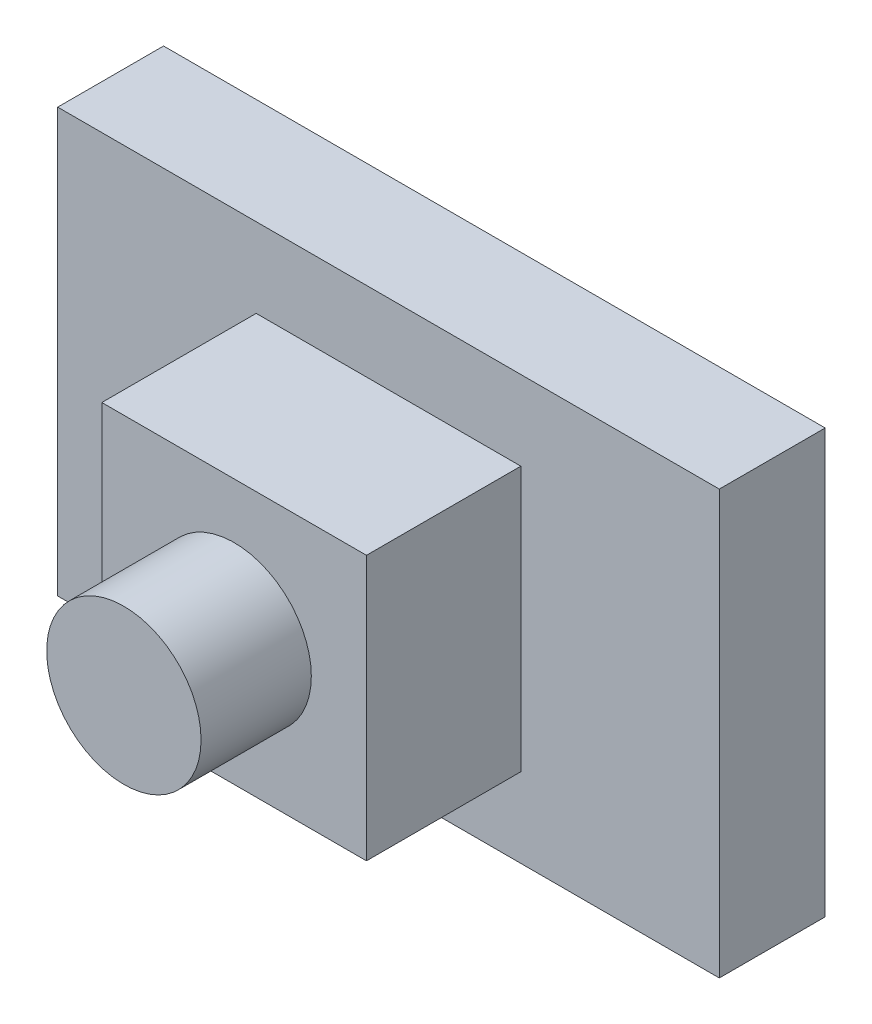
SolidWorks part; units mm, degrees
ref_plane "Ön Düzlem" through (0, 0, 0) normal (0, 0, 1) x (1, 0, 0)
ref_plane "Üst Düzlem" through (0, 0, 0) normal (0, 1, 0) x (1, 0, 0)
ref_plane "Sağ Düzlem" through (0, 0, 0) normal (1, 0, 0) x (0, 0, -1)
sketch "Çizim2" plane through (0, 0, 0) normal (0, 0, 1) x (1, 0, 0)
  line L1 (-7.5, -4.8) -> (7.5, -4.8)
  line L2 (-7.5, -4.8) -> (-7.5, 4.8)
  line L3 (-7.5, 4.8) -> (7.5, 4.8)
  line L4 (7.5, -4.8) -> (7.5, 4.8)
  line L5 (-7.5, -4.8) -> (7.5, 4.8) construction
  line L6 (-7.5, 4.8) -> (7.5, -4.8) construction
  point P0 (0, 0)
  dimension "D1" = 15
  dimension "D2" = 9.6
extrude "Yükseklik-Ekstrüzyon1" add sketch "Çizim2" along normal blind 2.4
sketch "Çizim3" plane through (0, 0, 2.4) normal (0, 0, 1) x (1, 0, 0)
  line L1 (-3, -3) -> (3, -3)
  line L2 (-3, -3) -> (-3, 3)
  line L3 (-3, 3) -> (3, 3)
  line L4 (3, -3) -> (3, 3)
  line L5 (-3, -3) -> (3, 3) construction
  line L6 (-3, 3) -> (3, -3) construction
  point P0 (0, 0)
  dimension "D1" = 6
  dimension "D2" = 6
extrude "Yükseklik-Ekstrüzyon2" add sketch "Çizim3" along normal blind 3.5
sketch "Çizim4" plane through (0, 0, 5.9) normal (0, 0, 1) x (1, 0, 0)
  circle A0 centre (0, 0) radius 1.75
  dimension "D1" = 3.5
extrude "Yükseklik-Ekstrüzyon3" add sketch "Çizim4" along normal blind 2.5
